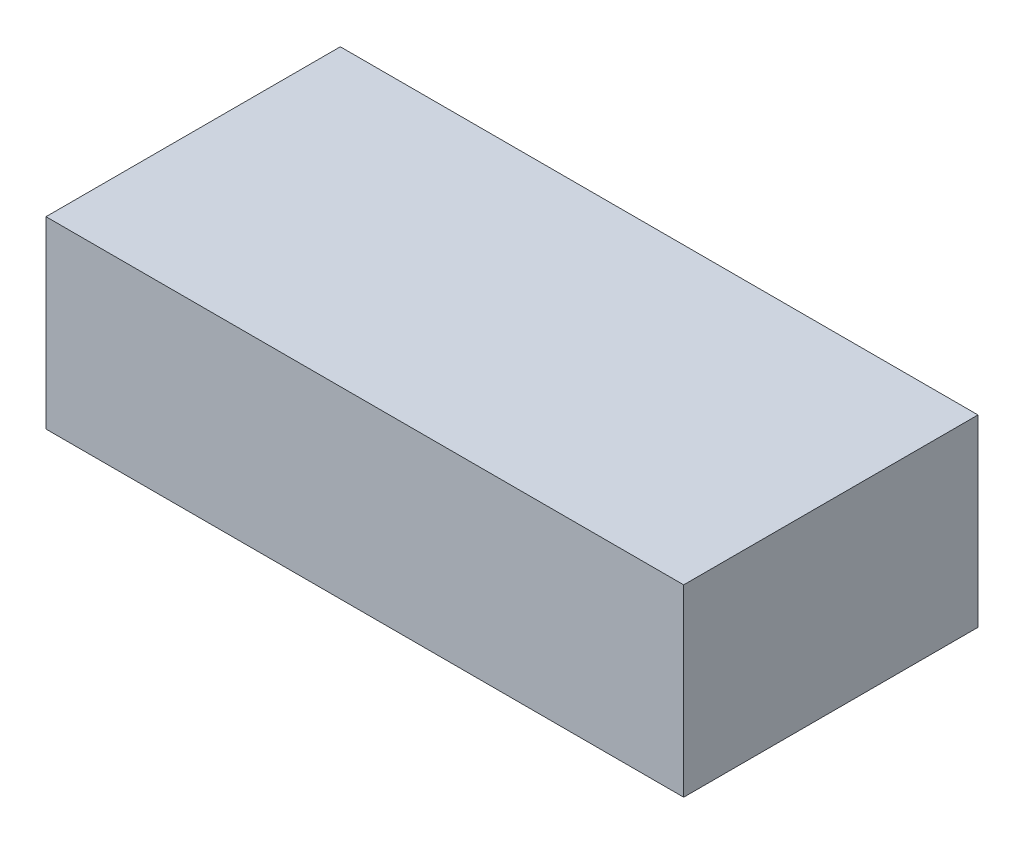
SolidWorks part; units mm, degrees
ref_plane "Front Plane" through (0, 0, 0) normal (0, 0, 1) x (1, 0, 0)
ref_plane "Top Plane" through (0, 0, 0) normal (0, 1, 0) x (1, 0, 0)
ref_plane "Right Plane" through (0, 0, 0) normal (1, 0, 0) x (0, 0, -1)
sketch "Sketch1" plane through (0, 0, 0) normal (0, 1, 0) x (1, 0, 0)
  line L1 (-26, -12) -> (26, -12)
  line L2 (-26, -12) -> (-26, 12)
  line L3 (-26, 12) -> (26, 12)
  line L4 (26, -12) -> (26, 12)
  line L5 (-26, -12) -> (26, 12) construction
  line L6 (-26, 12) -> (26, -12) construction
  point P0 (0, 0)
  dimension "D1" = 24
  dimension "D2" = 52
extrude "Boss-Extrude1" add sketch "Sketch1" along normal blind 15
